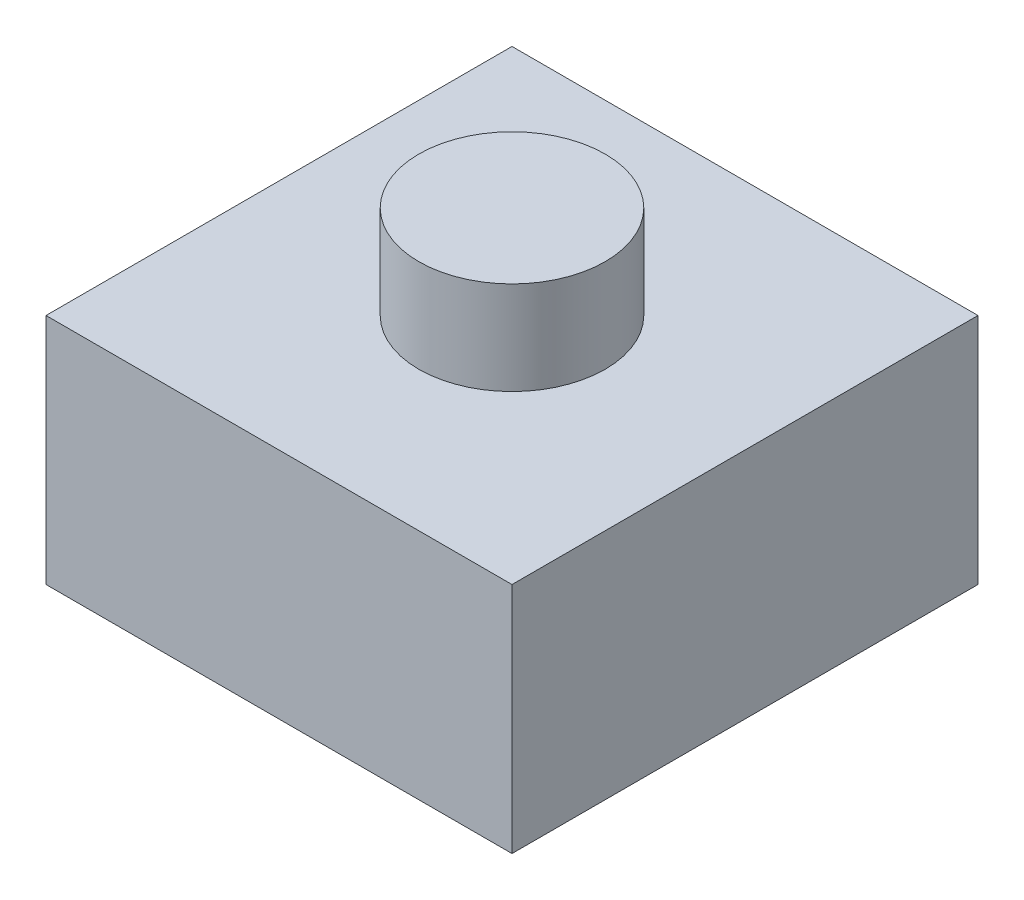
SolidWorks part; units mm, degrees
ref_plane "Front Plane" through (0, 0, 0) normal (0, 0, 1) x (1, 0, 0)
ref_plane "Top Plane" through (0, 0, 0) normal (0, 1, 0) x (1, 0, 0)
ref_plane "Right Plane" through (0, 0, 0) normal (1, 0, 0) x (0, 0, -1)
sketch "Sketch1" plane through (0, 0, 0) normal (0, 1, 0) x (1, 0, 0)
  line L1 (2.5, -2.5) -> (-2.5, -2.5)
  line L2 (2.5, -2.5) -> (2.5, 2.5)
  line L3 (2.5, 2.5) -> (-2.5, 2.5)
  line L4 (-2.5, -2.5) -> (-2.5, 2.5)
  line L5 (2.5, -2.5) -> (-2.5, 2.5) construction
  line L6 (2.5, 2.5) -> (-2.5, -2.5) construction
  point P0 (0, 0)
  dimension "D1" = 5
  dimension "D2" = 5
extrude "Boss-Extrude1" add sketch "Sketch1" along normal blind 2.5
sketch "Sketch2" plane through (0, 2.5, 0) normal (0, 1, 0) x (1, 0, 0)
  circle A0 centre (0, 0) radius 1
extrude "Boss-Extrude2" add sketch "Sketch2" along normal blind 1
